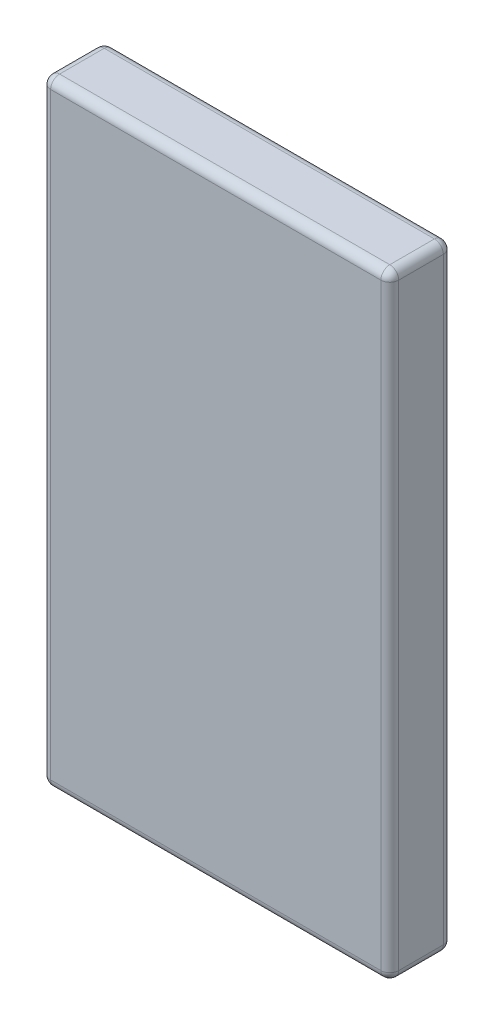
SolidWorks part; units mm, degrees
ref_plane "Front Plane" through (0, 0, 0) normal (0, 0, 1) x (1, 0, 0)
ref_plane "Top Plane" through (0, 0, 0) normal (0, 1, 0) x (1, 0, 0)
ref_plane "Right Plane" through (0, 0, 0) normal (1, 0, 0) x (0, 0, -1)
sketch "Sketch1" plane through (0, 0, 0) normal (0, 0, 1) x (1, 0, 0)
  line L1 (-16.3761, 55.7721) -> (22.6239, 55.7721)
  line L2 (-16.3761, 55.7721) -> (-16.3761, -13.2279)
  line L3 (-16.3761, -13.2279) -> (22.6239, -13.2279)
  line L4 (22.6239, 55.7721) -> (22.6239, -13.2279)
  dimension "D1" = 69
  dimension "D2" = 39
extrude "Boss-Extrude1" add sketch "Sketch1" along normal blind 7
fillet "Fillet1" radius 1 12 edges at (-16.3761, 21.2721, 0) (3.1239, -13.2279, 0) (22.6239, 21.2721, 0) (3.1239, 55.7721, 0) (3.1239, -13.2279, 7) (22.6239, 21.2721, 7) (-16.3761, 55.7721, 3.5) (22.6239, 55.7721, 3.5) (22.6239, -13.2279, 3.5) (-16.3761, -13.2279, 3.5) (3.1239, 55.7721, 7) (-16.3761, 21.2721, 7)
